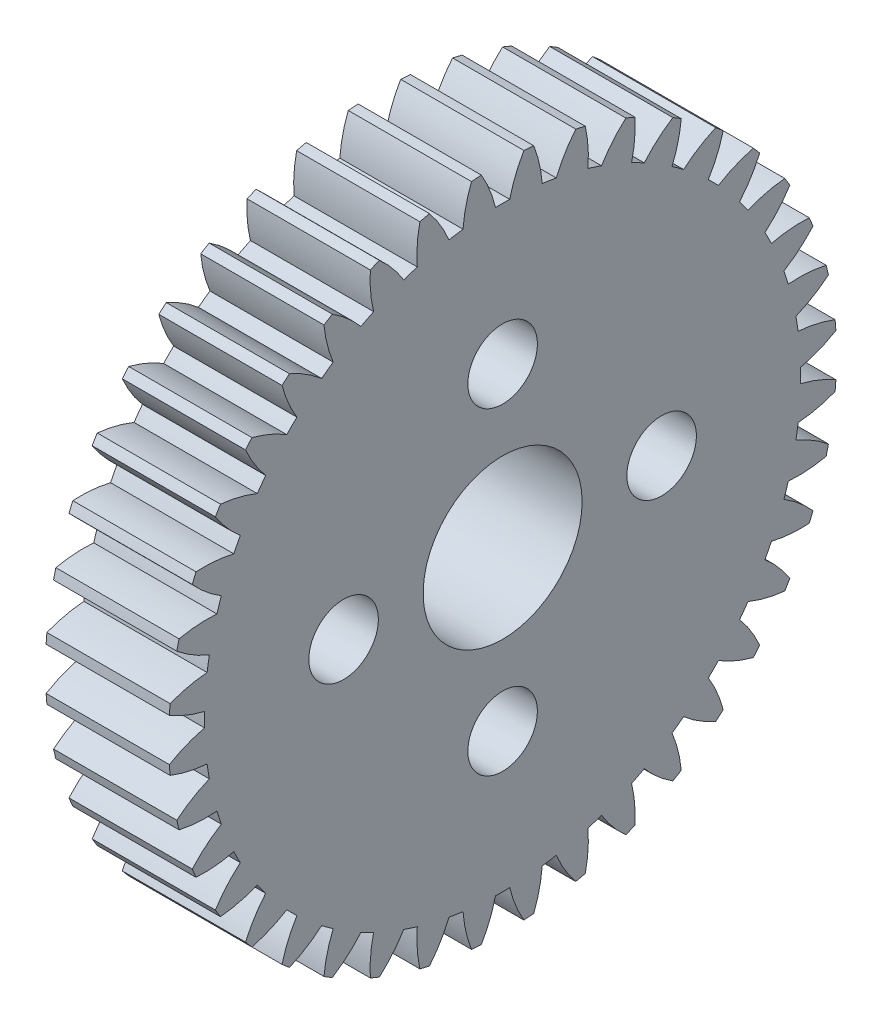
SolidWorks part; units mm, degrees
ref_plane "Front Plane" through (0, 0, 0) normal (0, 0, 1) x (1, 0, 0)
ref_plane "Top Plane" through (0, 0, 0) normal (0, 1, 0) x (1, 0, 0)
ref_plane "Right Plane" through (0, 0, 0) normal (1, 0, 0) x (0, 0, -1)
ref_plane "Plane1" through (0, 0, 0) normal (-1, 0, 0) x (0, -1, 0)
sketch "Sketch1" plane through (0, 0, 0) normal (-1, 0, 0) x (0, -1, 0)
  circle A0 centre (-8, 0) radius 1.75
  circle A1 centre (8, 0) radius 1.75
  circle A2 centre (0, -8) radius 1.75
  circle A3 centre (0, 8) radius 1.75
  circle A4 centre (0, 0) radius 4
  arc A5 (-16.3918, -3.681) -> (-16.2763, -4.1619) centre (0, 0) ccw
  arc A6 (-16.2763, -4.1619) -> (-14.3715, -4.2929) centre (-14.8897, 2.0861) ccw
  arc A7 (-14.3715, -4.2929) -> (-14.1501, -4.9743) centre (0, 0) ccw
  arc A8 (-14.1501, -4.9743) -> (-15.6141, -6.1999) centre (-10.8198, -10.4396) ccw
  arc A9 (-15.6141, -6.1999) -> (-15.4249, -6.6568) centre (0, 0) ccw
  arc A10 (-15.4249, -6.6568) -> (-13.523, -6.4883) centre (-15.0327, -0.2689) ccw
  arc A11 (-13.523, -6.4883) -> (-13.1978, -7.1267) centre (0, 0) ccw
  arc A12 (-13.1978, -7.1267) -> (-14.452, -8.5662) centre (-9.0535, -12.0037) ccw
  arc A13 (-14.452, -8.5662) -> (-14.1936, -8.9879) centre (0, 0) ccw
  arc A14 (-14.1936, -8.9879) -> (-12.3415, -8.5239) centre (-14.8055, -2.6172) ccw
  arc A15 (-12.3415, -8.5239) -> (-11.9204, -9.1035) centre (0, 0) ccw
  arc A16 (-11.9204, -9.1035) -> (-12.934, -10.7215) centre (-7.0643, -13.2721) ccw
  arc A17 (-12.934, -10.7215) -> (-12.6128, -11.0976) centre (0, 0) ccw
  arc A18 (-12.6128, -11.0976) -> (-10.8562, -10.3496) centre (-14.2138, -4.9011) ccw
  arc A19 (-10.8562, -10.3496) -> (-10.3496, -10.8562) centre (0, 0) ccw
  arc A20 (-10.3496, -10.8562) -> (-11.0976, -12.6128) centre (-4.9011, -14.2138) ccw
  arc A21 (-11.0976, -12.6128) -> (-10.7215, -12.934) centre (0, 0) ccw
  arc A22 (-10.7215, -12.934) -> (-9.1035, -11.9204) centre (-13.2721, -7.0643) ccw
  arc A23 (-9.1035, -11.9204) -> (-8.5239, -12.3415) centre (0, 0) ccw
  arc A24 (-8.5239, -12.3415) -> (-8.9879, -14.1936) centre (-2.6172, -14.8055) ccw
  arc A25 (-8.9879, -14.1936) -> (-8.5662, -14.452) centre (0, 0) ccw
  arc A26 (-8.5662, -14.452) -> (-7.1267, -13.1978) centre (-12.0037, -9.0535) ccw
  arc A27 (-7.1267, -13.1978) -> (-6.4883, -13.523) centre (0, 0) ccw
  arc A28 (-6.4883, -13.523) -> (-6.6568, -15.4249) centre (-0.2689, -15.0327) ccw
  arc A29 (-6.6568, -15.4249) -> (-6.1999, -15.6141) centre (0, 0) ccw
  arc A30 (-6.1999, -15.6141) -> (-4.9743, -14.1501) centre (-10.4396, -10.8198) ccw
  arc A31 (-4.9743, -14.1501) -> (-4.2929, -14.3715) centre (0, 0) ccw
  arc A32 (-4.2929, -14.3715) -> (-4.1619, -16.2763) centre (2.0861, -14.8897) ccw
  arc A33 (-4.1619, -16.2763) -> (-3.681, -16.3918) centre (0, 0) ccw
  arc A34 (-3.681, -16.3918) -> (-2.6995, -14.7541) centre (-8.6185, -12.3197) ccw
  arc A35 (-2.6995, -14.7541) -> (-1.9919, -14.8662) centre (0, 0) ccw
  arc A36 (-1.9919, -14.8662) -> (-1.5645, -16.727) centre (4.3896, -14.38) ccw
  arc A37 (-1.5645, -16.727) -> (-1.0715, -16.7658) centre (0, 0) ccw
  arc A38 (-1.0715, -16.7658) -> (-0.3582, -14.9947) centre (-6.5851, -13.5163) ccw
  arc A39 (-0.3582, -14.9947) -> (0.3582, -14.9947) centre (0, 0) ccw
  arc A40 (0.3582, -14.9947) -> (1.0715, -16.7658) centre (6.5851, -13.5163) ccw
  arc A41 (1.0715, -16.7658) -> (1.5645, -16.727) centre (0, 0) ccw
  arc A42 (1.5645, -16.727) -> (1.9919, -14.8662) centre (-4.3896, -14.38) ccw
  arc A43 (1.9919, -14.8662) -> (2.6995, -14.7541) centre (0, 0) ccw
  arc A44 (2.6995, -14.7541) -> (3.681, -16.3918) centre (8.6185, -12.3197) ccw
  arc A45 (3.681, -16.3918) -> (4.1619, -16.2763) centre (0, 0) ccw
  arc A46 (4.1619, -16.2763) -> (4.2929, -14.3715) centre (-2.0861, -14.8897) ccw
  arc A47 (4.2929, -14.3715) -> (4.9743, -14.1501) centre (0, 0) ccw
  arc A48 (4.9743, -14.1501) -> (6.1999, -15.6141) centre (10.4396, -10.8198) ccw
  arc A49 (6.1999, -15.6141) -> (6.6568, -15.4249) centre (0, 0) ccw
  arc A50 (6.6568, -15.4249) -> (6.4883, -13.523) centre (0.2689, -15.0327) ccw
  arc A51 (6.4883, -13.523) -> (7.1267, -13.1978) centre (0, 0) ccw
  arc A52 (7.1267, -13.1978) -> (8.5662, -14.452) centre (12.0037, -9.0535) ccw
  arc A53 (8.5662, -14.452) -> (8.9879, -14.1936) centre (0, 0) ccw
  arc A54 (8.9879, -14.1936) -> (8.5239, -12.3415) centre (2.6172, -14.8055) ccw
  arc A55 (8.5239, -12.3415) -> (9.1035, -11.9204) centre (0, 0) ccw
  arc A56 (9.1035, -11.9204) -> (10.7215, -12.934) centre (13.2721, -7.0643) ccw
  arc A57 (10.7215, -12.934) -> (11.0976, -12.6128) centre (0, 0) ccw
  arc A58 (11.0976, -12.6128) -> (10.3496, -10.8562) centre (4.9011, -14.2138) ccw
  arc A59 (10.3496, -10.8562) -> (10.8562, -10.3496) centre (0, 0) ccw
  arc A60 (10.8562, -10.3496) -> (12.6128, -11.0976) centre (14.2138, -4.9011) ccw
  arc A61 (12.6128, -11.0976) -> (12.934, -10.7215) centre (0, 0) ccw
  arc A62 (12.934, -10.7215) -> (11.9204, -9.1035) centre (7.0643, -13.2721) ccw
  arc A63 (11.9204, -9.1035) -> (12.3415, -8.5239) centre (0, 0) ccw
  arc A64 (12.3415, -8.5239) -> (14.1936, -8.9879) centre (14.8055, -2.6172) ccw
  arc A65 (14.1936, -8.9879) -> (14.452, -8.5662) centre (0, 0) ccw
  arc A66 (14.452, -8.5662) -> (13.1978, -7.1267) centre (9.0535, -12.0037) ccw
  arc A67 (13.1978, -7.1267) -> (13.523, -6.4883) centre (0, 0) ccw
  arc A68 (13.523, -6.4883) -> (15.4249, -6.6568) centre (15.0327, -0.2689) ccw
  arc A69 (15.4249, -6.6568) -> (15.6141, -6.1999) centre (0, 0) ccw
  arc A70 (15.6141, -6.1999) -> (14.1501, -4.9743) centre (10.8198, -10.4396) ccw
  arc A71 (14.1501, -4.9743) -> (14.3715, -4.2929) centre (0, 0) ccw
  arc A72 (14.3715, -4.2929) -> (16.2763, -4.1619) centre (14.8897, 2.0861) ccw
  arc A73 (16.2763, -4.1619) -> (16.3918, -3.681) centre (0, 0) ccw
  arc A74 (16.3918, -3.681) -> (14.7541, -2.6995) centre (12.3197, -8.6185) ccw
  arc A75 (14.7541, -2.6995) -> (14.8662, -1.9919) centre (0, 0) ccw
  arc A76 (14.8662, -1.9919) -> (16.727, -1.5645) centre (14.38, 4.3896) ccw
  arc A77 (16.727, -1.5645) -> (16.7658, -1.0715) centre (0, 0) ccw
  arc A78 (16.7658, -1.0715) -> (14.9947, -0.3582) centre (13.5163, -6.5851) ccw
  arc A79 (14.9947, -0.3582) -> (14.9947, 0.3582) centre (0, 0) ccw
  arc A80 (14.9947, 0.3582) -> (16.7658, 1.0715) centre (13.5163, 6.5851) ccw
  arc A81 (16.7658, 1.0715) -> (16.727, 1.5645) centre (0, 0) ccw
  arc A82 (16.727, 1.5645) -> (14.8662, 1.9919) centre (14.38, -4.3896) ccw
  arc A83 (14.8662, 1.9919) -> (14.7541, 2.6995) centre (0, 0) ccw
  arc A84 (14.7541, 2.6995) -> (16.3918, 3.681) centre (12.3197, 8.6185) ccw
  arc A85 (16.3918, 3.681) -> (16.2763, 4.1619) centre (0, 0) ccw
  arc A86 (16.2763, 4.1619) -> (14.3715, 4.2929) centre (14.8897, -2.0861) ccw
  arc A87 (14.3715, 4.2929) -> (14.1501, 4.9743) centre (0, 0) ccw
  arc A88 (14.1501, 4.9743) -> (15.6141, 6.1999) centre (10.8198, 10.4396) ccw
  arc A89 (15.6141, 6.1999) -> (15.4249, 6.6568) centre (0, 0) ccw
  arc A90 (15.4249, 6.6568) -> (13.523, 6.4883) centre (15.0327, 0.2689) ccw
  arc A91 (13.523, 6.4883) -> (13.1978, 7.1267) centre (0, 0) ccw
  arc A92 (13.1978, 7.1267) -> (14.452, 8.5662) centre (9.0535, 12.0037) ccw
  arc A93 (14.452, 8.5662) -> (14.1936, 8.9879) centre (0, 0) ccw
  arc A94 (14.1936, 8.9879) -> (12.3415, 8.5239) centre (14.8055, 2.6172) ccw
  arc A95 (12.3415, 8.5239) -> (11.9204, 9.1035) centre (0, 0) ccw
  arc A96 (11.9204, 9.1035) -> (12.934, 10.7215) centre (7.0643, 13.2721) ccw
  arc A97 (12.934, 10.7215) -> (12.6128, 11.0976) centre (0, 0) ccw
  arc A98 (12.6128, 11.0976) -> (10.8562, 10.3496) centre (14.2138, 4.9011) ccw
  arc A99 (10.8562, 10.3496) -> (10.3496, 10.8562) centre (0, 0) ccw
  arc A100 (10.3496, 10.8562) -> (11.0976, 12.6128) centre (4.9011, 14.2138) ccw
  arc A101 (11.0976, 12.6128) -> (10.7215, 12.934) centre (0, 0) ccw
  arc A102 (10.7215, 12.934) -> (9.1035, 11.9204) centre (13.2721, 7.0643) ccw
  arc A103 (9.1035, 11.9204) -> (8.5239, 12.3415) centre (0, 0) ccw
  arc A104 (8.5239, 12.3415) -> (8.9879, 14.1936) centre (2.6172, 14.8055) ccw
  arc A105 (8.9879, 14.1936) -> (8.5662, 14.452) centre (0, 0) ccw
  arc A106 (8.5662, 14.452) -> (7.1267, 13.1978) centre (12.0037, 9.0535) ccw
  arc A107 (7.1267, 13.1978) -> (6.4883, 13.523) centre (0, 0) ccw
  arc A108 (6.4883, 13.523) -> (6.6568, 15.4249) centre (0.2689, 15.0327) ccw
  arc A109 (6.6568, 15.4249) -> (6.1999, 15.6141) centre (0, 0) ccw
  arc A110 (6.1999, 15.6141) -> (4.9743, 14.1501) centre (10.4396, 10.8198) ccw
  arc A111 (4.9743, 14.1501) -> (4.2929, 14.3715) centre (0, 0) ccw
  arc A112 (4.2929, 14.3715) -> (4.1619, 16.2763) centre (-2.0861, 14.8897) ccw
  arc A113 (4.1619, 16.2763) -> (3.681, 16.3918) centre (0, 0) ccw
  arc A114 (3.681, 16.3918) -> (2.6995, 14.7541) centre (8.6185, 12.3197) ccw
  arc A115 (2.6995, 14.7541) -> (1.9919, 14.8662) centre (0, 0) ccw
  arc A116 (1.9919, 14.8662) -> (1.5645, 16.727) centre (-4.3896, 14.38) ccw
  arc A117 (1.5645, 16.727) -> (1.0715, 16.7658) centre (0, 0) ccw
  arc A118 (1.0715, 16.7658) -> (0.3582, 14.9947) centre (6.5851, 13.5163) ccw
  arc A119 (0.3582, 14.9947) -> (-0.3582, 14.9947) centre (0, 0) ccw
  arc A120 (-0.3582, 14.9947) -> (-1.0715, 16.7658) centre (-6.5851, 13.5163) ccw
  arc A121 (-1.0715, 16.7658) -> (-1.5645, 16.727) centre (0, 0) ccw
  arc A122 (-1.5645, 16.727) -> (-1.9919, 14.8662) centre (4.3896, 14.38) ccw
  arc A123 (-1.9919, 14.8662) -> (-2.6995, 14.7541) centre (0, 0) ccw
  arc A124 (-2.6995, 14.7541) -> (-3.681, 16.3918) centre (-8.6185, 12.3197) ccw
  arc A125 (-3.681, 16.3918) -> (-4.1619, 16.2763) centre (0, 0) ccw
  arc A126 (-4.1619, 16.2763) -> (-4.2929, 14.3715) centre (2.0861, 14.8897) ccw
  arc A127 (-4.2929, 14.3715) -> (-4.9743, 14.1501) centre (0, 0) ccw
  arc A128 (-4.9743, 14.1501) -> (-6.1999, 15.6141) centre (-10.4396, 10.8198) ccw
  arc A129 (-6.1999, 15.6141) -> (-6.6568, 15.4249) centre (0, 0) ccw
  arc A130 (-6.6568, 15.4249) -> (-6.4883, 13.523) centre (-0.2689, 15.0327) ccw
  arc A131 (-6.4883, 13.523) -> (-7.1267, 13.1978) centre (0, 0) ccw
  arc A132 (-7.1267, 13.1978) -> (-8.5662, 14.452) centre (-12.0037, 9.0535) ccw
  arc A133 (-8.5662, 14.452) -> (-8.9879, 14.1936) centre (0, 0) ccw
  arc A134 (-8.9879, 14.1936) -> (-8.5239, 12.3415) centre (-2.6172, 14.8055) ccw
  arc A135 (-8.5239, 12.3415) -> (-9.1035, 11.9204) centre (0, 0) ccw
  arc A136 (-9.1035, 11.9204) -> (-10.7215, 12.934) centre (-13.2721, 7.0643) ccw
  arc A137 (-10.7215, 12.934) -> (-11.0976, 12.6128) centre (0, 0) ccw
  arc A138 (-11.0976, 12.6128) -> (-10.3496, 10.8562) centre (-4.9011, 14.2138) ccw
  arc A139 (-10.3496, 10.8562) -> (-10.8562, 10.3496) centre (0, 0) ccw
  arc A140 (-10.8562, 10.3496) -> (-12.6128, 11.0976) centre (-14.2138, 4.9011) ccw
  arc A141 (-12.6128, 11.0976) -> (-12.934, 10.7215) centre (0, 0) ccw
  arc A142 (-12.934, 10.7215) -> (-11.9204, 9.1035) centre (-7.0643, 13.2721) ccw
  arc A143 (-11.9204, 9.1035) -> (-12.3415, 8.5239) centre (0, 0) ccw
  arc A144 (-12.3415, 8.5239) -> (-14.1936, 8.9879) centre (-14.8055, 2.6172) ccw
  arc A145 (-14.1936, 8.9879) -> (-14.452, 8.5662) centre (0, 0) ccw
  arc A146 (-14.452, 8.5662) -> (-13.1978, 7.1267) centre (-9.0535, 12.0037) ccw
  arc A147 (-13.1978, 7.1267) -> (-13.523, 6.4883) centre (0, 0) ccw
  arc A148 (-13.523, 6.4883) -> (-15.4249, 6.6568) centre (-15.0327, 0.2689) ccw
  arc A149 (-15.4249, 6.6568) -> (-15.6141, 6.1999) centre (0, 0) ccw
  arc A150 (-15.6141, 6.1999) -> (-14.1501, 4.9743) centre (-10.8198, 10.4396) ccw
  arc A151 (-14.1501, 4.9743) -> (-14.3715, 4.2929) centre (0, 0) ccw
  arc A152 (-14.3715, 4.2929) -> (-16.2763, 4.1619) centre (-14.8897, -2.0861) ccw
  arc A153 (-16.2763, 4.1619) -> (-16.3918, 3.681) centre (0, 0) ccw
  arc A154 (-16.3918, 3.681) -> (-14.7541, 2.6995) centre (-12.3197, 8.6185) ccw
  arc A155 (-14.7541, 2.6995) -> (-14.8662, 1.9919) centre (0, 0) ccw
  arc A156 (-14.8662, 1.9919) -> (-16.727, 1.5645) centre (-14.38, -4.3896) ccw
  arc A157 (-16.727, 1.5645) -> (-16.7658, 1.0715) centre (0, 0) ccw
  arc A158 (-16.7658, 1.0715) -> (-14.9947, 0.3582) centre (-13.5163, 6.5851) ccw
  arc A159 (-14.9947, 0.3582) -> (-14.9947, -0.3582) centre (0, 0) ccw
  arc A160 (-14.9947, -0.3582) -> (-16.7658, -1.0715) centre (-13.5163, -6.5851) ccw
  arc A161 (-16.7658, -1.0715) -> (-16.727, -1.5645) centre (0, 0) ccw
  arc A162 (-16.727, -1.5645) -> (-14.8662, -1.9919) centre (-14.38, 4.3896) ccw
  arc A163 (-14.8662, -1.9919) -> (-14.7541, -2.6995) centre (0, 0) ccw
  arc A164 (-14.7541, -2.6995) -> (-16.3918, -3.681) centre (-12.3197, -8.6185) ccw
extrude "Boss-Extrude1" add sketch "Sketch1" against normal blind 6.2
